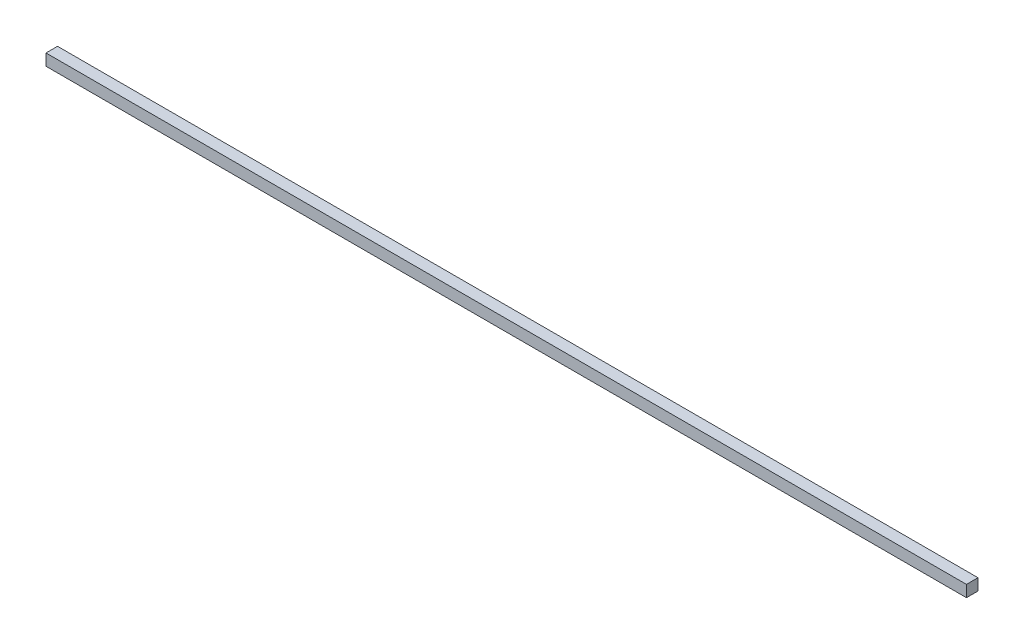
SolidWorks part; units mm, degrees
ref_plane "Front Plane" through (0, 0, 0) normal (0, 0, 1) x (1, 0, 0)
ref_plane "Top Plane" through (0, 0, 0) normal (0, 1, 0) x (1, 0, 0)
ref_plane "Right Plane" through (0, 0, 0) normal (1, 0, 0) x (0, 0, -1)
other "Configuration Table"
sketch "Sketch1" plane through (0, 0, 0) normal (0, 0, 1) x (1, 0, 0)
  line L1 (59, 408) -> (697, 408)
  line L2 (59, 408) -> (59, 416)
  line L3 (59, 416) -> (697, 416)
  line L4 (697, 408) -> (697, 416)
extrude "STORE_klape_kaset_kati_pivot_mil_1" add sketch "Sketch1" against normal blind 8 separate body
